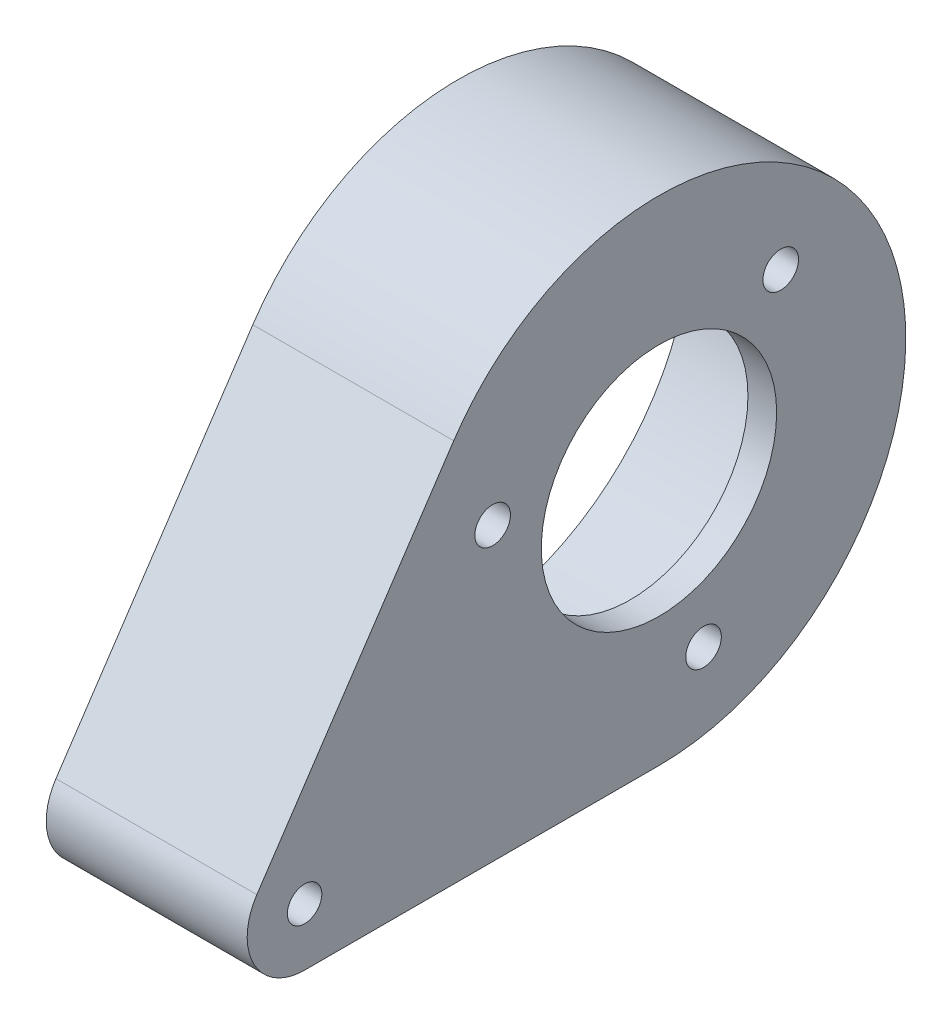
SolidWorks part; units mm, degrees
material "ABS"
ref_plane "Спереди" through (0, 0, 0) normal (0, 0, 1) x (1, 0, 0)
ref_plane "Сверху" through (0, 0, 0) normal (0, 1, 0) x (1, 0, 0)
ref_plane "Справа" through (0, 0, 0) normal (1, 0, 0) x (0, 0, -1)
sketch "Эскиз1" plane through (0, 0, 0) normal (1, 0, 0) x (0, 0, -1)
  line L0 (-30.8666, -21.5) -> (0, -21.5)
  line L1 (-30.8666, -16.5) -> (0, 0) construction
  line L2 (-35.0242, -13.7224) -> (-17.8775, 11.9435)
  arc A0 (0, -21.5) -> (-17.8775, 11.9435) centre (0, 0) ccw
  arc A1 (-35.0242, -13.7224) -> (-30.8666, -21.5) centre (-30.8666, -16.5) ccw
  dimension "D1" = 43
  dimension "D2" = 10
  dimension "D3" = 35
extrude "Бобышка-Вытянуть1" add sketch "Эскиз1" along normal blind 2.5
sketch "Эскиз2" plane through (0, 0, 0) normal (-1, 0, 0) x (0, 0, 1)
  line L0 (0, -21.5) -> (30.8666, -21.5)
  line L1 (17.8775, 11.9435) -> (35.0242, -13.7224)
  arc A0 (17.8775, 11.9435) -> (0, -21.5) centre (0, 0) ccw
  circle A1 centre (0, 0) radius 20.25
  circle A2 centre (0, 0) radius 21.5 construction
  arc A3 (30.8666, -21.5) -> (35.0242, -13.7224) centre (30.8666, -16.5) ccw
  arc A4 (30.8666, -21.5) -> (35.0242, -13.7224) centre (30.8666, -16.5) ccw construction
  dimension "D1" = 40.5
extrude "Бобышка-Вытянуть2" add sketch "Эскиз2" along normal blind 15
sketch "Эскиз3" plane through (2.5, 0, 0) normal (1, 0, 0) x (0, 0, -1)
  line L0 (0, 0) -> (0, 15) construction
  line L1 (0, 0) -> (0, -15) construction
  line L2 (0, 0) -> (10.6066, 10.6066) construction
  line L4 (0, 0) -> (-15, 0) construction
  circle A0 centre (0, 0) radius 15 construction
  circle A1 centre (10.6066, 10.6066) radius 1.55
  circle A2 centre (3.8823, -14.4889) radius 1.55
  circle A3 centre (-14.4889, 3.8823) radius 1.55
  circle A4 centre (0, 0) radius 10.25
  point P13 (0, 0)
  dimension "D1" = 30
  dimension "D2" = 3.1
  dimension "D5" = 20.5
  dimension "D4" = 135
  dimension "D3" = 3
extrude "Вырез-Вытянуть1" cut sketch "Эскиз3" against normal up to surface (2.5 mm away) up to face at (0, 0, 20.25)
sketch "Эскиз5" plane through (-15, 0, 0) normal (-1, 0, 0) x (0, 0, 1)
  circle A0 centre (30.8666, -16.5) radius 1.5
  arc A1 (30.8666, -21.5) -> (35.0242, -13.7224) centre (30.8666, -16.5) ccw construction
  dimension "D1" = 3
extrude "Вырез-Вытянуть2" cut sketch "Эскиз5" against normal through all
